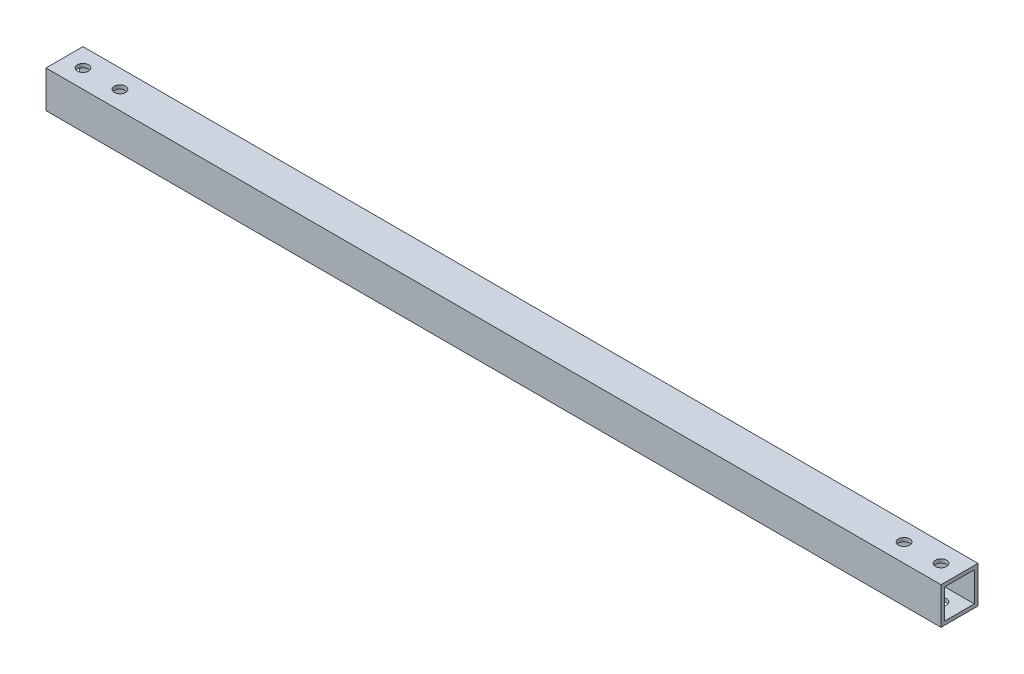
SolidWorks part; units mm, degrees
material "1060 Alloy"
ref_plane "Front Plane" through (0, 0, 0) normal (0, 0, 1) x (1, 0, 0)
ref_plane "Top Plane" through (0, 0, 0) normal (0, 1, 0) x (1, 0, 0)
ref_plane "Right Plane" through (0, 0, 0) normal (1, 0, 0) x (0, 0, -1)
sketch "Sketch1" plane through (0, 0, 0) normal (1, 0, 0) x (0, 0, -1)
  line L0 (8, 8) -> (-8, 8)
  line L1 (-8, 8) -> (-8, -8)
  line L2 (0, 0) -> (0, 27.1676) construction
  line L3 (0, 0) -> (-28.5263, 0) construction
  line L4 (8, 8) -> (8, -8)
  line L5 (8, -8) -> (-8, -8)
  line L7 (-10, 10) -> (10, 10)
  line L8 (-10, 10) -> (-10, -10)
  line L9 (-10, -10) -> (10, -10)
  line L10 (10, 10) -> (10, -10)
  point P8 (0, 8)
  point P11 (8, 0)
  point P12 (-8, 0)
  dimension "D1" = 16
  dimension "D2" = 20
  dimension "D3" = 10
  dimension "D4" = 10
extrude "Boss-Extrude1" add sketch "Sketch1" along normal mid plane 484
sketch "Sketch2" plane through (0, 10, 0) normal (0, 1, 0) x (1, 0, 0)
  line L0 (0, 0) -> (252.2759, 0) construction
  line L1 (242, 10) -> (242, -10) construction
  line L2 (-242, 10) -> (-242, -10) construction
  circle A0 centre (212, 0) radius 3
  circle A1 centre (232, 0) radius 3
  circle A2 centre (-232, 0) radius 3
  circle A3 centre (-212, 0) radius 3
  point P13 (-242, 0)
  dimension "D1" = 6
  dimension "D2" = 20
  dimension "D3" = 10
  dimension "D4" = 20
  dimension "D5" = 10
extrude "Cut-Extrude1" cut sketch "Sketch2" against normal through all
